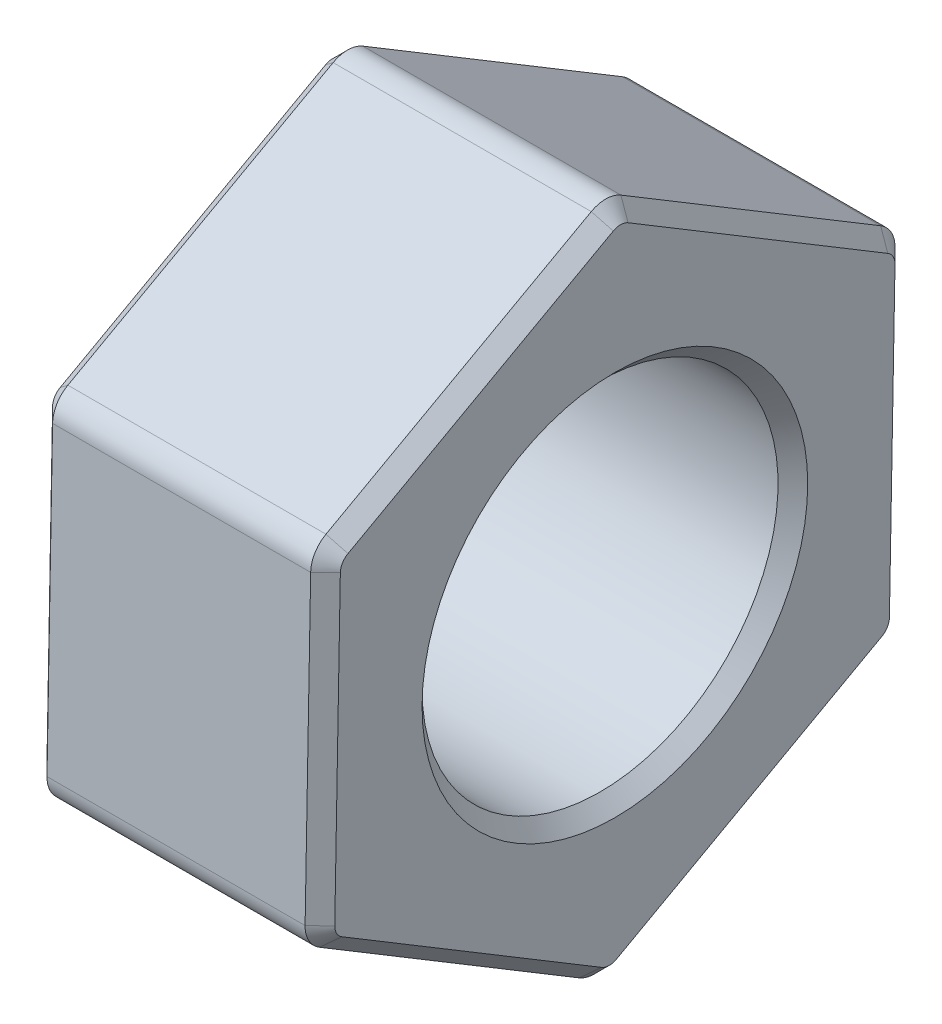
SolidWorks part; units mm, degrees
ref_plane "Front Plane" through (0, 0, 0) normal (0, 0, 1) x (1, 0, 0)
ref_plane "Top Plane" through (0, 0, 0) normal (0, 1, 0) x (1, 0, 0)
ref_plane "Right Plane" through (0, 0, 0) normal (1, 0, 0) x (0, 0, -1)
sketch "Sketch1" plane through (0, 0, 0) normal (1, 0, 0) x (0, 0, -1)
  line L1 (4.7291, 2.9014) -> (0.3518, 5.537)
  line L2 (-0.1481, 5.5462) -> (-4.6193, 3.0732)
  line L3 (-4.8772, 2.6449) -> (-4.9711, -2.4638)
  line L4 (-4.7291, -2.9014) -> (-0.3518, -5.537)
  line L5 (0.1481, -5.5462) -> (4.6193, -3.0732)
  line L6 (4.8772, -2.6449) -> (4.9711, 2.4638)
  circle A0 centre (0, 0) radius 4.925 construction
  circle A1 centre (0, 0) radius 3
  arc A2 (4.7291, 2.9014) -> (4.9711, 2.4638) centre (4.4712, 2.473) cw
  arc A3 (4.8772, -2.6449) -> (4.6193, -3.0732) centre (4.3773, -2.6357) cw
  arc A4 (0.1481, -5.5462) -> (-0.3518, -5.537) centre (-0.0939, -5.1087) cw
  arc A5 (-4.7291, -2.9014) -> (-4.9711, -2.4638) centre (-4.4712, -2.473) cw
  arc A6 (-4.8772, 2.6449) -> (-4.6193, 3.0732) centre (-4.3773, 2.6357) cw
  arc A7 (0.3518, 5.537) -> (-0.1481, 5.5462) centre (0.0939, 5.1087) ccw
  dimension "D1" = 9.85
  dimension "D2" = 0.5
extrude "Boss-Extrude1" add sketch "Sketch1" along normal blind 4.85
chamfer "Chamfer1" distance 0.25 angle 45 26 edges at (0, 0, -3) (0, 4.2192, -2.5405) (0, 5.6086, -0.1031) (0, 4.3097, 2.3837) (0, 2.8936, 4.8056) (0, 0.0905, 4.9242) (0, -2.715, 4.9087) (0, -4.2192, 2.5405) (0, -5.6086, 0.1031) (0, -4.3097, -2.3837) (0, -2.8936, -4.8056) (0, -0.0905, -4.9242) (0, 2.715, -4.9087) (4.85, 0, -3) (4.85, -0.0905, -4.9242) (4.85, -2.8936, -4.8056) (4.85, -4.3097, -2.3837) (4.85, -5.6086, 0.1031) (4.85, -4.2192, 2.5405) (4.85, -2.715, 4.9087) (4.85, 0.0905, 4.9242) (4.85, 2.8936, 4.8056) (4.85, 4.3097, 2.3837) (4.85, 5.6086, -0.1031) (4.85, 4.2192, -2.5405) (4.85, 2.715, -4.9087)
